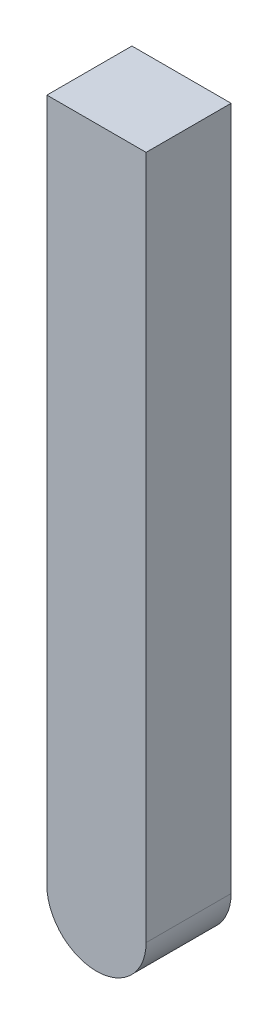
SolidWorks part; units mm, degrees
material "Cobre"
ref_plane "Plano frontal" through (0, 0, 0) normal (0, 0, 1) x (1, 0, 0)
ref_plane "Plano superior" through (0, 0, 0) normal (0, 1, 0) x (1, 0, 0)
ref_plane "Plano direito" through (0, 0, 0) normal (1, 0, 0) x (0, 0, -1)
sketch "Esboço1" plane through (0, 0, 0) normal (0, 0, 1) x (1, 0, 0)
  line L0 (-0.35, 2.415) -> (-0.35, -2.415)
  line L1 (0.35, -2.415) -> (0.35, 2.415)
  line L2 (0.35, 2.415) -> (-0.35, 2.415)
  line L3 (0, 2.415) -> (0, 0) construction
  line L4 (0, 0) -> (0.35, 0) construction
  arc A0 (-0.35, -2.415) -> (0.35, -2.415) centre (0, -2.415) ccw
  dimension "D1" = 0.7
  dimension "D2" = 4.83
extrude "Ressalto-extrusão1" add sketch "Esboço1" along normal mid plane 0.6
